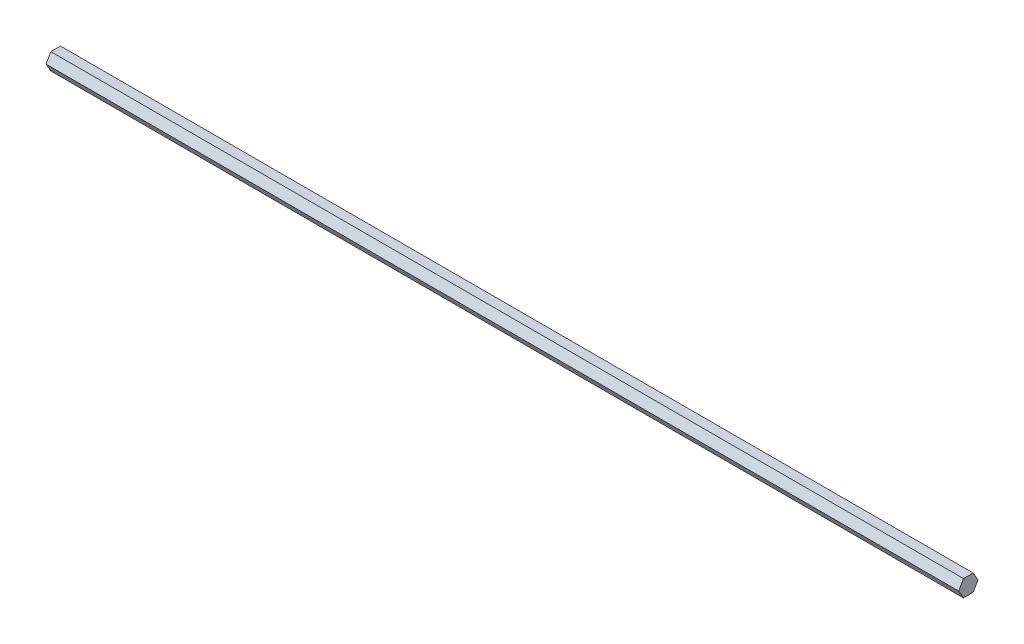
SolidWorks part; units mm, degrees
material "7075-T6 (SN)"
ref_plane "Front Plane" through (0, 0, 0) normal (0, 0, 1) x (1, 0, 0)
ref_plane "Top Plane" through (0, 0, 0) normal (0, 1, 0) x (1, 0, 0)
ref_plane "Right Plane" through (0, 0, 0) normal (1, 0, 0) x (0, 0, -1)
sketch "Sketch1" plane through (0, 0, 0) normal (1, 0, 0) x (0, 0, -1)
  line L1 (7.3323, 0) -> (3.6662, 6.35)
  line L2 (3.6662, 6.35) -> (-3.6662, 6.35)
  line L3 (-3.6662, 6.35) -> (-7.3323, 0)
  line L4 (-7.3323, 0) -> (-3.6662, -6.35)
  line L5 (-3.6662, -6.35) -> (3.6662, -6.35)
  line L6 (3.6662, -6.35) -> (7.3323, 0)
  circle A0 centre (0, 0) radius 6.35 construction
  dimension "D1" = 12.7
extrude "Boss-Extrude1" add sketch "Sketch1" along normal blind 692.15
sketch "Sketch2" plane through (0, 0, 0) normal (-1, 0, 0) x (0, 0, 1)
  circle A0 centre (0, 0) radius 4.0239 construction
